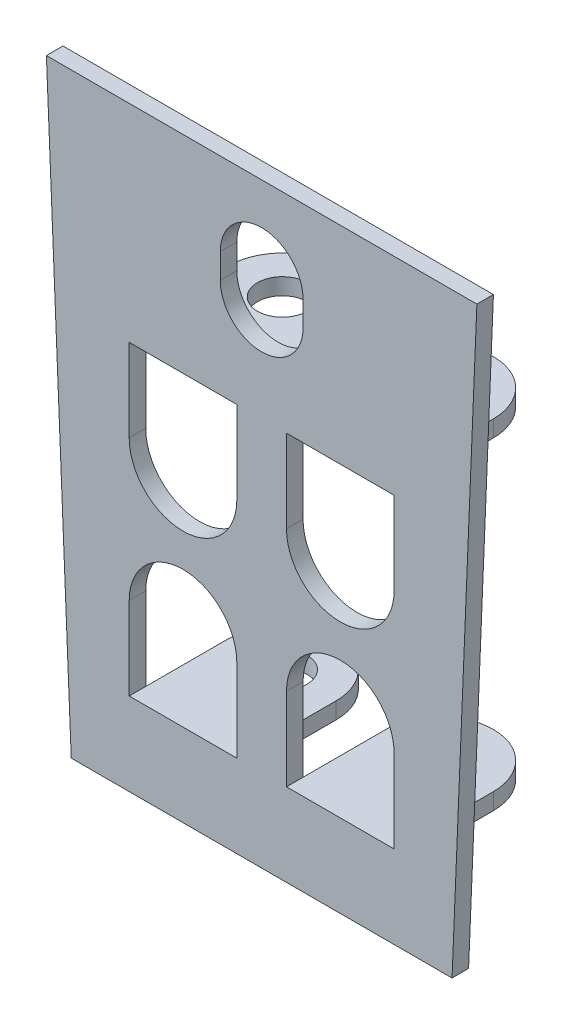
SolidWorks part; units mm, degrees
ref_plane "前视基准面" through (0, 0, 0) normal (0, 0, 1) x (1, 0, 0)
ref_plane "上视基准面" through (0, 0, 0) normal (0, 1, 0) x (1, 0, 0)
ref_plane "右视基准面" through (0, 0, 0) normal (1, 0, 0) x (0, 0, -1)
sketch "草图1" plane through (0, 0, 0) normal (0, 0, 1) x (1, 0, 0)
  line L0 (-22.6697, 47.6986) -> (-22.6697, -114.5938) construction
  line L1 (-48.6697, 16.3557) -> (3.3303, 16.3557)
  line L2 (3.3303, 16.3557) -> (0.3303, -55.6443)
  line L3 (0.3303, -55.6443) -> (-45.6697, -55.6443)
  line L4 (-45.6697, -55.6443) -> (-48.6697, 16.3557)
  line L5 (-22.6697, 3.3557) -> (-22.6697, 6.3557) construction
  line L6 (-27.6697, 3.3557) -> (-27.6697, 6.3557)
  line L7 (-17.6697, 3.3557) -> (-17.6697, 6.3557)
  line L8 (-38.6697, -8.6443) -> (-25.6697, -8.6443)
  line L9 (-6.6697, -8.6443) -> (-6.6697, -18.6443)
  line L10 (-19.6697, -8.6443) -> (-6.6697, -8.6443)
  line L11 (-19.6697, -8.6443) -> (-19.6697, -18.6443)
  line L12 (-38.6697, -8.6443) -> (-38.6697, -18.6443)
  line L13 (-25.6697, -8.6443) -> (-38.6697, -8.6443)
  line L14 (-25.6697, -8.6443) -> (-25.6697, -18.6443)
  line L15 (-38.6697, -27.1443) -> (-4.253, -27.1443) construction
  line L16 (-6.6697, -45.6443) -> (-6.6697, -35.6443)
  line L17 (-19.6697, -45.6443) -> (-6.6697, -45.6443)
  line L18 (-19.6697, -45.6443) -> (-19.6697, -35.6443)
  line L19 (-25.6697, -45.6443) -> (-25.6697, -35.6443)
  line L20 (-38.6697, -45.6443) -> (-25.6697, -45.6443)
  line L21 (-38.6697, -45.6443) -> (-38.6697, -35.6443)
  arc A0 (-27.6697, 3.3557) -> (-17.6697, 3.3557) centre (-22.6697, 3.3557) ccw
  arc A1 (-17.6697, 6.3557) -> (-27.6697, 6.3557) centre (-22.6697, 6.3557) ccw
  arc A2 (-19.6697, -18.6443) -> (-6.6697, -18.6443) centre (-13.1697, -18.6443) ccw
  arc A3 (-25.6697, -18.6443) -> (-38.6697, -18.6443) centre (-32.1697, -18.6443) cw
  arc A4 (-19.6697, -35.6443) -> (-6.6697, -35.6443) centre (-13.1697, -35.6443) cw
  arc A5 (-25.6697, -35.6443) -> (-38.6697, -35.6443) centre (-32.1697, -35.6443) ccw
  point P7 (-22.6697, 4.8557)
  point P15 (-22.6697, -1.6443)
  dimension "D4" = 5
  dimension "D6" = 10
  dimension "D9" = 8.5
  dimension "D1" = 46
  dimension "D2" = 52
  dimension "D3" = 72
  dimension "D5" = 3
  dimension "D7" = 7
  dimension "D8" = 13
  dimension "D11" = 10
extrude "凸台-拉伸1" add sketch "草图1" along normal blind 2 contours L4 L3 L2 L1 A5 L19 L20 L21 A2 L11 L10 L9 A1 L7 A0 L6 L14 A3 L12 L8 L18 A4 L16 L17
ref_plane "基准面1" through (0, -8.6443, 0) normal (0, -1, 0) x (-1, 0, 0)
sketch "草图2" plane through (0, -8.6443, 0) normal (0, -1, 0) x (-1, 0, 0)
  line L0 (6.6697, 0) -> (6.6697, 10)
  line L1 (19.6697, 0) -> (19.6697, 10)
  line L2 (25.6697, 0) -> (25.6697, 10)
  line L3 (38.6697, 0) -> (38.6697, 10)
  line L4 (6.6697, 0) -> (19.6697, 0)
  line L5 (25.6697, 0) -> (38.6697, 0)
  arc A0 (6.6697, 10) -> (19.6697, 10) centre (13.1697, 10) cw
  circle A1 centre (13.1697, 10) radius 3
  arc A2 (25.6697, 10) -> (38.6697, 10) centre (32.1697, 10) cw
  circle A3 centre (32.1697, 10) radius 3
  dimension "D2" = 6
  dimension "D3" = 6
  dimension "D1" = 10
extrude "凸台-拉伸2" add sketch "草图2" against normal blind 2 contours A2 L2 L5 L3 A3 | A0 L0 L4 L1 A1
ref_plane "基准面2" through (0, -27.1443, 0) normal (0, -1, 0) x (-1, 0, 0)
mirror "镜向2" about plane through (0, -27.1443, 0) normal (0, -1, 0) of "凸台-拉伸2"
